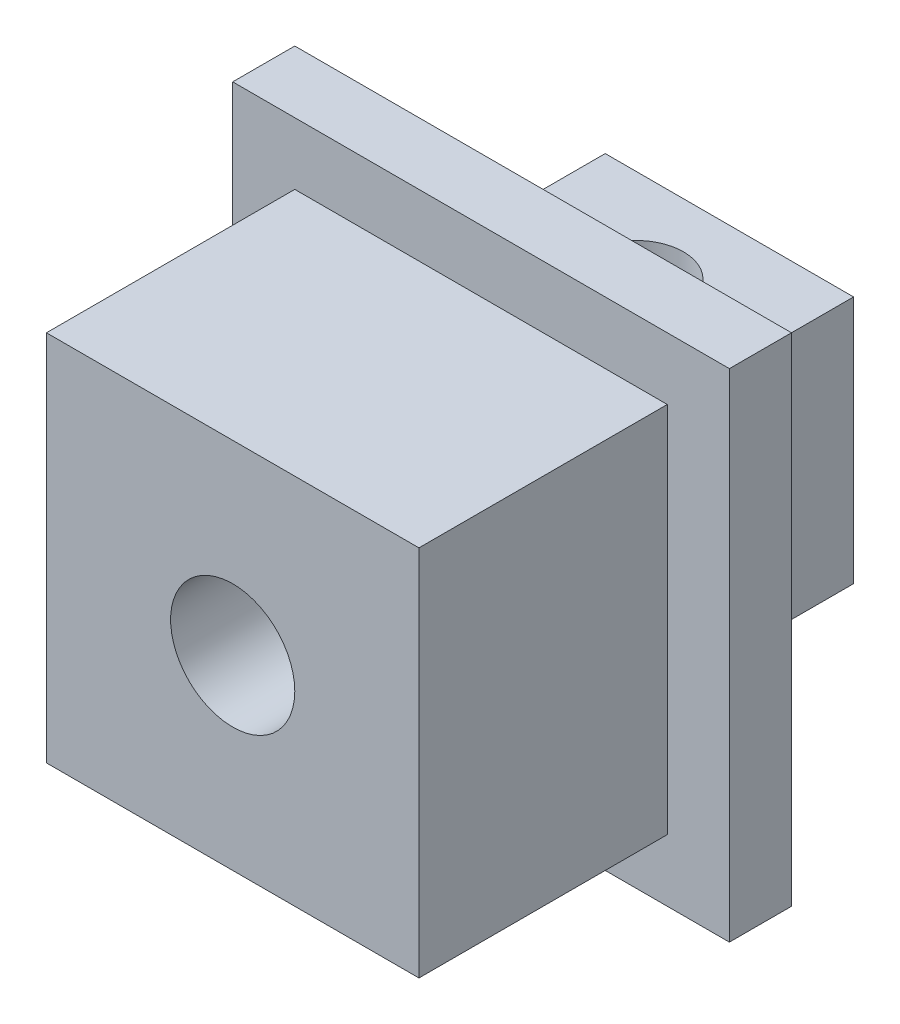
SolidWorks part; units mm, degrees
ref_plane "Front Plane" through (0, 0, 0) normal (0, 0, 1) x (1, 0, 0)
ref_plane "Top Plane" through (0, 0, 0) normal (0, 1, 0) x (1, 0, 0)
ref_plane "Right Plane" through (0, 0, 0) normal (1, 0, 0) x (0, 0, -1)
sketch "Sketch2" plane through (0, 0, 0) normal (0, 0, 1) x (1, 0, 0)
  line L1 (0, 0) -> (19.05, 0)
  line L2 (0, 0) -> (0, 19.05)
  line L3 (0, 19.05) -> (19.05, 19.05)
  line L4 (19.05, 0) -> (19.05, 19.05)
  circle A0 centre (9.525, 9.525) radius 3.175
  dimension "D3" = 9.525
  dimension "D4" = 9.525
  dimension "D5" = 6.35
  dimension "D1" = 19.05
  dimension "D2" = 19.05
extrude "Boss-Extrude1" add sketch "Sketch2" along normal blind 12.7
sketch "Sketch3" plane through (0, 0, 0) normal (0, 0, -1) x (-1, 0, 0)
  line L0 (0, 0) -> (-19.05, 0) construction
  line L1 (3.175, -3.175) -> (-22.225, -3.175)
  line L2 (3.175, -3.175) -> (3.175, 22.225)
  line L3 (3.175, 22.225) -> (-22.225, 22.225)
  line L4 (-22.225, -3.175) -> (-22.225, 22.225)
  line L5 (0, 19.05) -> (0, 0) construction
  dimension "D1" = 25.4
  dimension "D2" = 25.4
  dimension "D3" = 3.175
  dimension "D4" = 3.175
extrude "Boss-Extrude2" add sketch "Sketch3" along normal blind 3.175
sketch "Sketch4" plane through (0, 0, -3.175) normal (0, 0, -1) x (-1, 0, 0)
  line L0 (3.175, -3.175) -> (3.175, 22.225) construction
  line L1 (-3.175, 3.175) -> (-15.875, 3.175)
  line L2 (-3.175, 3.175) -> (-3.175, 15.875)
  line L3 (-3.175, 15.875) -> (-15.875, 15.875)
  line L4 (-15.875, 3.175) -> (-15.875, 15.875)
  line L5 (3.175, 22.225) -> (-22.225, 22.225) construction
  dimension "D1" = 12.7
  dimension "D2" = 12.7
  dimension "D3" = 6.35
  dimension "D4" = 6.35
extrude "Boss-Extrude3" add sketch "Sketch4" along normal blind 9.525
sketch "Sketch5" plane through (0, 0, 12.7) normal (0, 0, 1) x (1, 0, 0)
  circle A0 centre (9.525, 9.525) radius 3.175 construction
  circle A1 centre (9.525, 9.525) radius 3.175
extrude "Cut-Extrude1" cut sketch "Sketch5" against normal through all
sketch "Sketch6" plane through (0, 15.875, 0) normal (0, 1, 0) x (1, 0, 0)
  line L0 (15.875, 12.7) -> (15.875, 3.175) construction
  line L1 (3.175, 12.7) -> (15.875, 12.7) construction
  circle A0 centre (9.525, 7.9375) radius 2.413
  dimension "D1" = 6.35
  dimension "D2" = 4.7625
  dimension "D3" = 4.826
extrude "Cut-Extrude2" cut sketch "Sketch6" against normal blind 6.35
